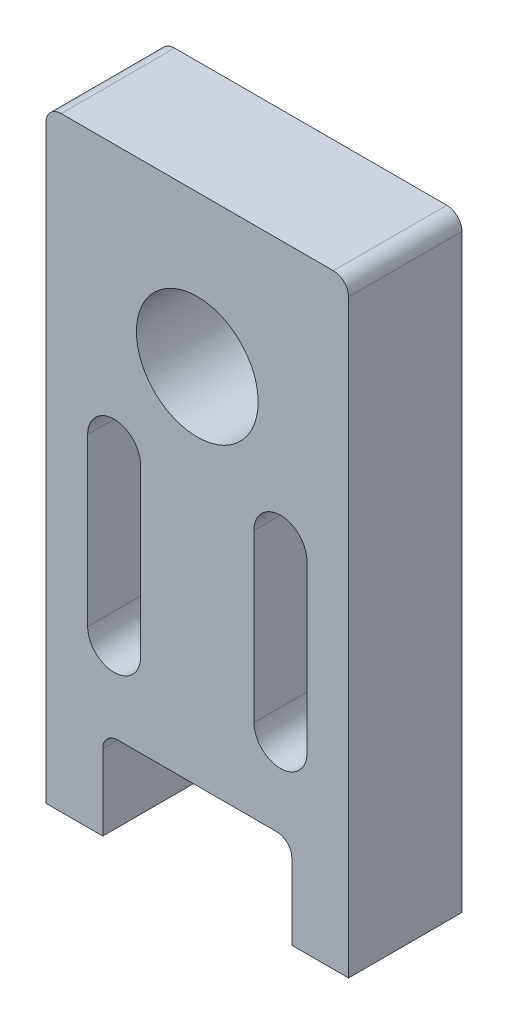
SolidWorks part; units mm, degrees
ref_plane "前视基准面" through (0, 0, 0) normal (0, 0, 1) x (1, 0, 0)
ref_plane "上视基准面" through (0, 0, 0) normal (0, 1, 0) x (1, 0, 0)
ref_plane "右视基准面" through (0, 0, 0) normal (1, 0, 0) x (0, 0, -1)
sketch "草图1" plane through (0, 0, 0) normal (0, 0, 1) x (1, 0, 0)
  line L1 (-20, -40) -> (20, -40)
  line L2 (-20, -40) -> (-20, 40)
  line L3 (-20, 40) -> (20, 40)
  line L4 (20, -40) -> (20, 40)
  line L5 (-20, -40) -> (20, 40) construction
  line L6 (-20, 40) -> (20, -40) construction
  point P0 (0, 0)
  dimension "D1" = 80
  dimension "D2" = 40
extrude "凸台-拉伸1" add sketch "草图1" along normal blind 15
sketch "草图2" plane through (0, 0, 15) normal (0, 0, 1) x (1, 0, 0)
  line L0 (0, 43.9214) -> (0, -52.137) construction
  line L1 (-20, -40) -> (20, -40) construction
  circle A0 centre (0, 20) radius 8.05
  dimension "D1" = 60
  dimension "D2" = 16.1
extrude "切除-拉伸1" cut sketch "草图2" against normal blind 60
sketch "草图3" plane through (0, 0, 15) normal (0, 0, 1) x (1, 0, 0)
  line L0 (0, 0) -> (0, -43.7035) construction
  line L1 (-20, -40) -> (20, -40) construction
  line L2 (-12.5, -44.9694) -> (12.5, -44.9694)
  line L3 (-12.5, -44.9694) -> (-12.5, -28)
  line L4 (-12.5, -28) -> (12.5, -28)
  line L5 (12.5, -44.9694) -> (12.5, -28)
  line L6 (-12.5, -44.9694) -> (12.5, -28) construction
  line L7 (-12.5, -28) -> (12.5, -44.9694) construction
  point P3 (0, -36.4847)
  dimension "D1" = 25
  dimension "D2" = 12
extrude "切除-拉伸2" cut sketch "草图3" against normal blind 60
sketch "草图4" plane through (0, -28, 0) normal (0, -1, 0) x (1, 0, 0)
  line L0 (-12.5, 7.5) -> (12.5, 7.5) construction
  line L1 (-12.5, 0) -> (-12.5, 15) construction
  line L2 (12.5, 0) -> (12.5, 15) construction
  circle A0 centre (0, 7.5) radius 1.45
  dimension "D1" = 2.9
extrude "切除-拉伸3" cut sketch "草图4" against normal blind 35
sketch "草图5" plane through (0, 0, 15) normal (0, 0, 1) x (1, 0, 0)
  line L0 (0, 44.8167) -> (0, -46.6073) construction
  line L6 (-11, 5) -> (-11, -17) construction
  line L7 (-7.5, 5) -> (-7.5, -17)
  line L12 (-14.5, 5) -> (-14.5, -17)
  line L13 (11, 5) -> (11, -17) construction
  line L14 (14.5, 5) -> (14.5, -17)
  line L15 (7.5, 5) -> (7.5, -17)
  line L16 (12.5, -28) -> (-12.5, -28) construction
  arc A0 (-7.5, 5) -> (-14.5, 5) centre (-11, 5) ccw
  arc A1 (-14.5, -17) -> (-7.5, -17) centre (-11, -17) ccw
  arc A2 (14.5, 5) -> (7.5, 5) centre (11, 5) ccw
  arc A3 (7.5, -17) -> (14.5, -17) centre (11, -17) ccw
  point P5 (-11, -6)
  point P10 (11, -6)
  dimension "D3" = 7
  dimension "D1" = 11
  dimension "D2" = 11
  dimension "D4" = 7
  dimension "D5" = 11
  dimension "D6" = 11
  dimension "D7" = 22
  dimension "D8" = 22
extrude "切除-拉伸4" cut sketch "草图5" against normal blind 35
fillet "圆角1" radius 2 4 edges at (20, 40, 7.5) (-20, 40, 7.5) (12.5, -28, 7.5) (-12.5, -28, 7.5)
